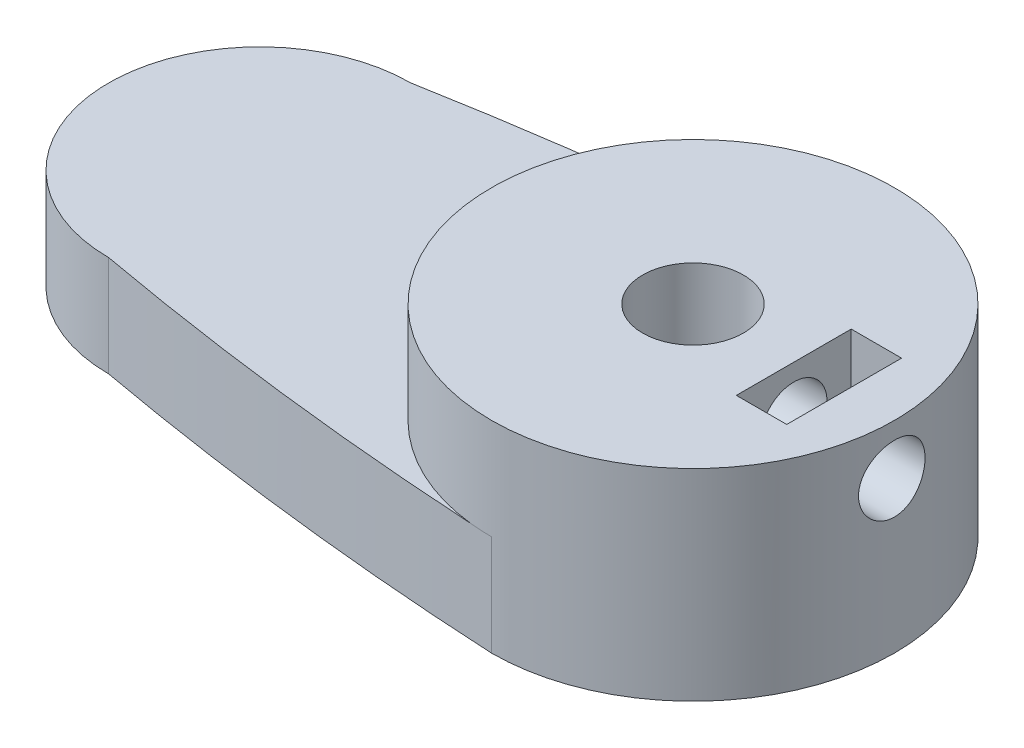
SolidWorks part; units mm, degrees
ref_plane "Front Plane" through (0, 0, 0) normal (0, 0, 1) x (1, 0, 0)
ref_plane "Top Plane" through (0, 0, 0) normal (0, 1, 0) x (1, 0, 0)
ref_plane "Right Plane" through (0, 0, 0) normal (1, 0, 0) x (0, 0, -1)
sketch "Sketch1" plane through (0, 0, 0) normal (0, 1, 0) x (1, 0, 0)
  line L0 (0, 0) -> (-29, 0) construction
  circle A0 centre (0, 0) radius 29 construction
  circle A1 centre (0, 0) radius 2.5
  arc A2 (-1.0861, -9.9408) -> (-1.0861, 9.9408) centre (0, 0) ccw
  arc A3 (-21.5, 7.5) -> (-21.5, -7.5) centre (-21.5, 0) ccw
  arc A4 (-21.5, 7.5) -> (0, 10) centre (8.5763, -157.4558) cw
  arc A5 (-21.5, -7.5) -> (0, -10) centre (8.5763, 157.4558) ccw
  point P14 (0, 0)
  dimension "D1" = 58
  dimension "D2" = 5
  dimension "D3" = 20
  dimension "D4" = 15
extrude "Boss-Extrude1" add sketch "Sketch1" along normal blind 5 contours A3 A5 A2 A4 A1
sketch "Sketch2" plane through (0, 5, 0) normal (0, 1, 0) x (1, 0, 0)
  circle A0 centre (0, 0) radius 10
  circle A1 centre (0, 0) radius 2.5
extrude "Boss-Extrude2" add sketch "Sketch2" along normal blind 5
sketch "Sketch3" plane through (0, 10, 0) normal (0, 1, 0) x (1, 0, 0)
  line L0 (0, 0) -> (12.5, 0) construction
  line L1 (12.5, 0) -> (14.4755, -6.5026) construction
  line L2 (14.4755, -6.5026) -> (14.4755, -6.6124) construction
  line L4 (5, -2.85) -> (7.5, -2.85)
  line L5 (5, -2.85) -> (5, 2.85)
  line L6 (5, 2.85) -> (7.5, 2.85)
  line L7 (7.5, -2.85) -> (7.5, 2.85)
  line L8 (5, -2.85) -> (7.5, 2.85) construction
  line L9 (5, 2.85) -> (7.5, -2.85) construction
  point P3 (6.25, 0)
  dimension "D1" = 2.5
  dimension "D2" = 5.7
  dimension "D3" = 5
extrude "Cut-Extrude1" cut sketch "Sketch3" against normal blind 5
sketch "Sketch4" plane through (0, 0, 0) normal (1, 0, 0) x (0, 0, -1)
  line L0 (-2.85, 10) -> (2.85, 10) construction
  circle A0 centre (0, 7.5) radius 1.65
  dimension "D1" = 3.3
  dimension "D2" = 2.5
extrude "Cut-Extrude2" cut sketch "Sketch4" along normal blind 25
